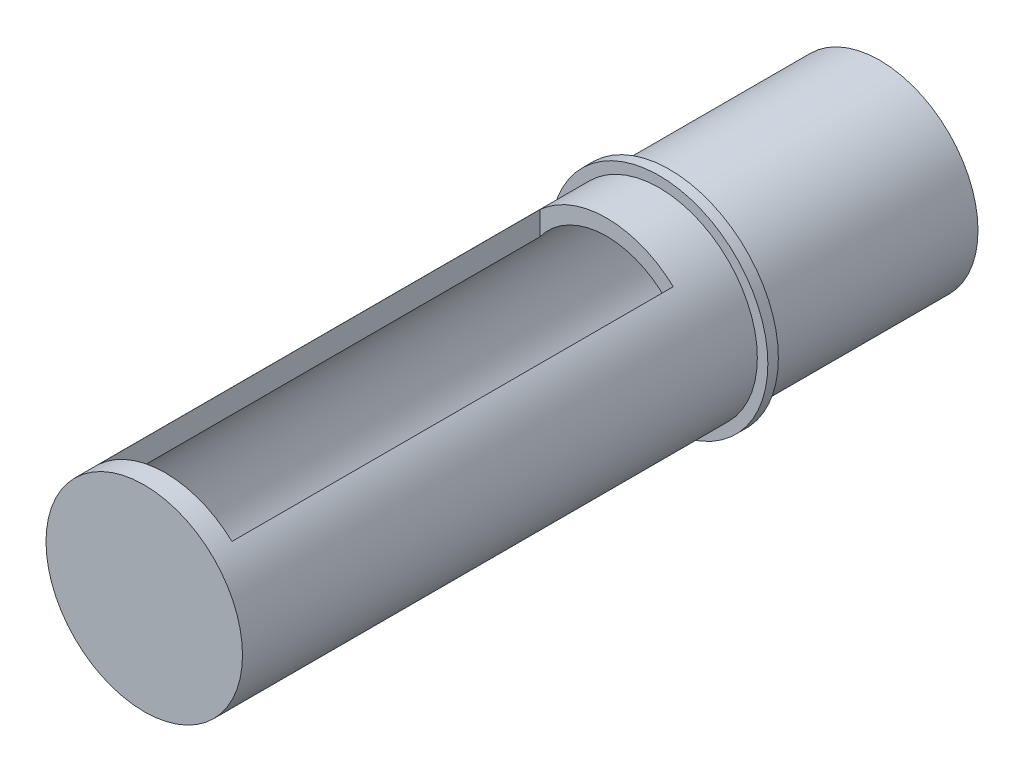
SolidWorks part; units mm, degrees
ref_plane "Front Plane" through (0, 0, 0) normal (0, 0, 1) x (1, 0, 0)
ref_plane "Top Plane" through (0, 0, 0) normal (0, 1, 0) x (1, 0, 0)
ref_plane "Right Plane" through (0, 0, 0) normal (1, 0, 0) x (0, 0, -1)
sketch "Esboço1" plane through (0, 0, 0) normal (0, 0, 1) x (1, 0, 0)
  circle A0 centre (0, 0) radius 9.35
  circle A1 centre (0, 0) radius 7.85
  dimension "D1" = 18.7
  dimension "D2" = 1.5
extrude "Ressalto-extrusão1" add sketch "Esboço1" along normal blind 50 and the other way blind 20
sketch "Esboço2" plane through (0, 0, 0) normal (0, 0, 1) x (1, 0, 0)
  circle A0 centre (0, 0) radius 10.35
  circle A1 centre (0, 0) radius 9.35
  circle A2 centre (0, 0) radius 9.35
  dimension "D2" = 1
  dimension "D1" = 0
extrude "Ressalto-extrusão2" add sketch "Esboço2" along normal blind 1
sketch "Esboço3" plane through (0, 0, 50) normal (0, 0, 1) x (1, 0, 0)
  circle A0 centre (0, 0) radius 7.85 construction
  circle A1 centre (0, 0) radius 7.85
extrude "Ressalto-extrusão3" add sketch "Esboço3" against normal blind 2
sketch "Esboço4" plane through (0, 0, 0) normal (0, 1, 0) x (1, 0, 0)
  line L0 (0, 0) -> (0, -50) construction
  line L1 (-9.35, -50) -> (9.35, -50) construction
  line L2 (-10.35, -1) -> (10.35, -1) construction
  line L3 (-6.35, -48) -> (6.35, -48)
  line L4 (-6.35, -48) -> (-6.35, -6)
  line L5 (-6.35, -6) -> (6.35, -6)
  line L6 (6.35, -48) -> (6.35, -6)
  line L7 (-6.35, -48) -> (6.35, -6) construction
  line L8 (-6.35, -6) -> (6.35, -48) construction
  point P5 (0, -27)
  dimension "D1" = 2
  dimension "D2" = 12.7
  dimension "D3" = 5
extrude "Corte-extrusão1" cut sketch "Esboço4" along normal blind 21
